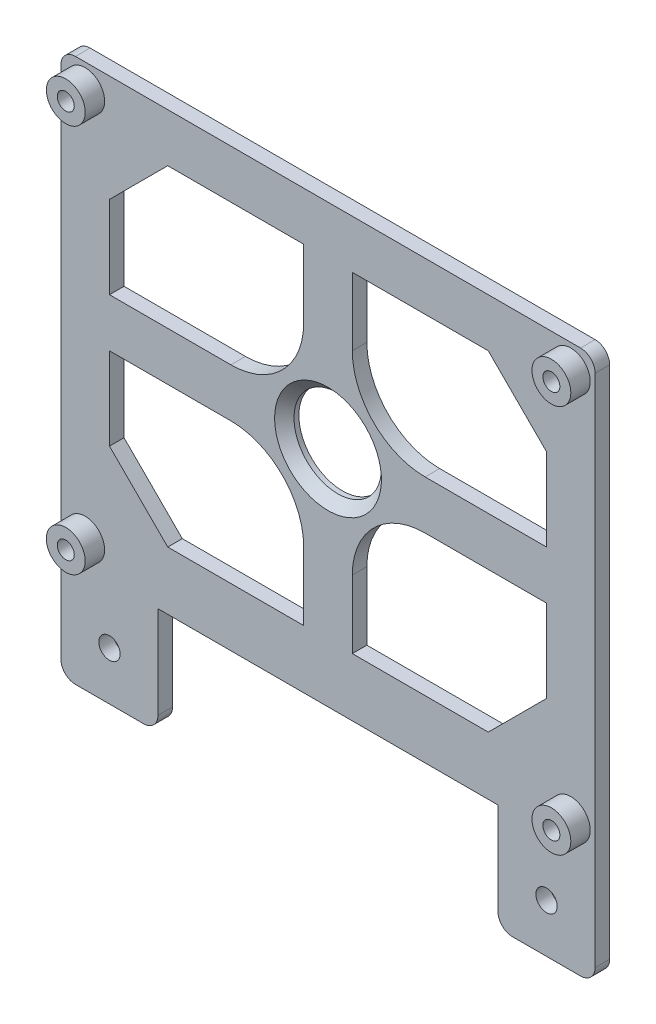
SolidWorks part; units mm, degrees
material "ABS"
ref_plane "Front Plane" through (0, 0, 0) normal (0, 0, 1) x (1, 0, 0)
ref_plane "Top Plane" through (0, 0, 0) normal (0, 1, 0) x (1, 0, 0)
ref_plane "Right Plane" through (0, 0, 0) normal (1, 0, 0) x (0, 0, -1)
sketch "Sketch1" plane through (0, 0, 0) normal (0, 0, 1) x (1, 0, 0)
  line L1 (55, 56) -> (-55, 56)
  line L2 (55, 56) -> (55, -56)
  line L3 (55, -56) -> (-55, -56)
  line L4 (-55, 56) -> (-55, -56)
  line L5 (55, 56) -> (-55, -56) construction
  line L6 (55, -56) -> (-55, 56) construction
  point P0 (0, 0)
  dimension "D1" = 110
  dimension "D2" = 112
extrude "Boss-Extrude1" add sketch "Sketch1" along normal blind 3
sketch "Sketch2" plane through (0, 0, 3) normal (0, 0, 1) x (1, 0, 0)
  line L0 (-55, -56) -> (55, -56) construction
  line L1 (-35, -56) -> (35, -56)
  line L2 (-35, -56) -> (-35, -34)
  line L3 (-35, -34) -> (35, -34)
  line L4 (35, -56) -> (35, -34)
  line L5 (0, -34) -> (0, 56) construction
  line L6 (55, 56) -> (-55, 56) construction
  circle A0 centre (0, 12) radius 9
  dimension "D3" = 18
  dimension "D4" = 68
  dimension "D1" = 70
  dimension "D2" = 22
extrude "Cut-Extrude1" cut sketch "Sketch2" against normal through all
sketch "Sketch3" plane through (0, 0, 3) normal (0, 0, 1) x (1, 0, 0)
  line L0 (-33, 46) -> (-5, 46)
  line L1 (-5, 46) -> (-5, 32)
  line L2 (-45, 17) -> (-20, 17)
  line L3 (0, 12) -> (0, 53.5825) construction
  line L4 (0, 12) -> (-45.232, 12) construction
  line L5 (-45, 17) -> (-45, 34)
  line L6 (-55, 56) -> (-55, -56) construction
  line L7 (55, 56) -> (-55, 56) construction
  line L8 (-45, 34) -> (-33, 46)
  line L9 (45, 34) -> (33, 46)
  line L10 (45, 17) -> (45, 34)
  line L11 (45, 17) -> (20, 17)
  line L12 (5, 46) -> (5, 32)
  line L13 (33, 46) -> (5, 46)
  line L14 (33, -22) -> (5, -22)
  line L15 (5, -22) -> (5, -8)
  line L16 (45, 7) -> (20, 7)
  line L17 (45, 7) -> (45, -10)
  line L18 (45, -10) -> (33, -22)
  line L19 (-45, -10) -> (-33, -22)
  line L20 (-45, 7) -> (-45, -10)
  line L21 (-45, 7) -> (-20, 7)
  line L22 (-5, -22) -> (-5, -8)
  line L23 (-33, -22) -> (-5, -22)
  arc A0 (-5, 32) -> (-20, 17) centre (-20, 32) cw
  arc A1 (-20, 7) -> (-5, -8) centre (-20, -8) cw
  arc A2 (5, -8) -> (20, 7) centre (20, -8) cw
  arc A3 (20, 17) -> (5, 32) centre (20, 32) cw
  point P31 (-5, 17)
  point P34 (-5, 7)
  point P37 (5, 7)
  point P40 (5, 17)
  dimension "D7" = 15
  dimension "D1" = 5
  dimension "D2" = 5
  dimension "D3" = 10
  dimension "D4" = 10
  dimension "D5" = 17
  dimension "D6" = 45
extrude "Cut-Extrude2" cut sketch "Sketch3" against normal through all
chamfer "Chamfer1" distance 2 angle 45 1 edges at (9, 12, 3)
sketch "Sketch4" plane through (0, 0, 3) normal (0, 0, 1) x (1, 0, 0)
  line L0 (-55, 56) -> (-55, -56) construction
  line L1 (55, 56) -> (-55, 56) construction
  line L2 (55, -56) -> (55, 56) construction
  circle A0 centre (-50, -29) radius 4
  circle A1 centre (50, -29) radius 4
  circle A2 centre (50, 51) radius 4
  circle A3 centre (-50, 51) radius 4
  dimension "D1" = 8
  dimension "D2" = 5
  dimension "D3" = 5
  dimension "D4" = 5
  dimension "D5" = 80
extrude "Boss-Extrude2" add sketch "Sketch4" along normal blind 4
sketch "Sketch5" plane through (0, 0, 7) normal (0, 0, 1) x (1, 0, 0)
  circle A0 centre (-50, 51) radius 1.75
  circle A1 centre (50, 51) radius 1.75
  circle A2 centre (50, -29) radius 1.75
  circle A3 centre (-50, -29) radius 1.75
  dimension "D1" = 3.5
extrude "Cut-Extrude3" cut sketch "Sketch5" against normal through all
fillet "Fillet1" radius 3 6 edges at (55, 56, 1.5) (55, -56, 1.5) (35, -56, 1.5) (-35, -56, 1.5) (-55, -56, 1.5) (-55, 56, 1.5)
sketch "Sketch6" plane through (0, 0, 3) normal (0, 0, 1) x (1, 0, 0)
  line L0 (-52, -56) -> (-38, -56) construction
  line L1 (-45, -46) -> (-45, -56) construction
  line L2 (45, -46) -> (45, -56) construction
  line L3 (38, -56) -> (52, -56) construction
  circle A0 centre (-45, -46) radius 2.2
  circle A1 centre (45, -46) radius 2.2
  dimension "D1" = 4.4
  dimension "D2" = 10
extrude "Cut-Extrude4" cut sketch "Sketch6" against normal through all
